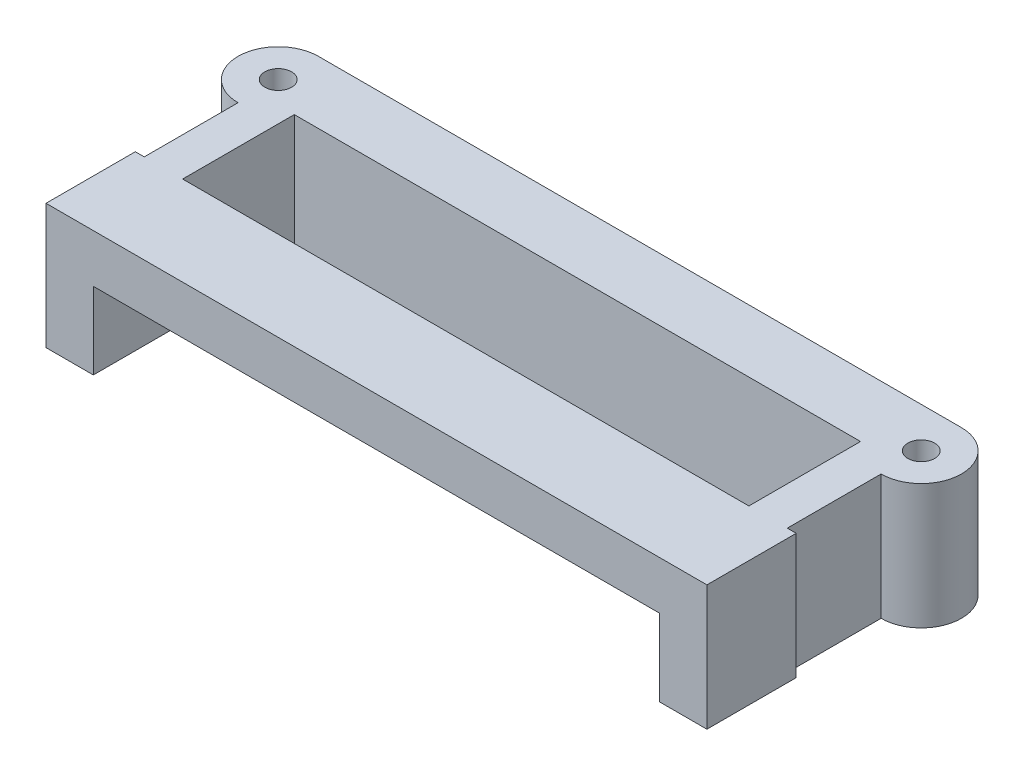
SolidWorks part; units mm, degrees
ref_plane "Спереди" through (0, 0, 0) normal (0, 0, 1) x (1, 0, 0)
ref_plane "Сверху" through (0, 0, 0) normal (0, 1, 0) x (1, 0, 0)
ref_plane "Справа" through (0, 0, 0) normal (1, 0, 0) x (0, 0, -1)
other "Configuration Table"
sketch "Эскиз1" plane through (0, 0, 0) normal (0, 1, 0) x (1, 0, 0)
  line L1 (0, 0) -> (1, 0)
  line L2 (0, 0) -> (0, -10)
  line L3 (0, -10) -> (74, -10)
  line L4 (74, 0) -> (74, -10)
  line L9 (1, 10.5) -> (1, 0)
  line L10 (73, 0) -> (74, 0)
  line L11 (73, 10.5) -> (73, 0)
  line L14 (5.3, 12.5) -> (5.3, 0)
  line L15 (5.3, 0) -> (68.7, 0)
  line L16 (68.7, 12.5) -> (68.7, 0)
  line L17 (1, 19.5) -> (73, 19.5)
  line L19 (5.3, 12.5) -> (68.7, 12.5)
  circle A0 centre (1, 15) radius 1.5
  circle A1 centre (73, 15) radius 1.5
  arc A2 (1, 19.5) -> (1, 10.5) centre (1, 15) ccw
  arc A3 (73, 10.5) -> (73, 19.5) centre (73, 15) ccw
  dimension "D3" = 3
  dimension "D4" = 3
  dimension "D8" = 9
  dimension "D9" = 9
  dimension "D1" = 74
  dimension "D2" = 10
  dimension "D5" = 72
  dimension "D6" = 1
  dimension "D7" = 15
  dimension "D10" = 12.5
  dimension "D11" = 5.3
  dimension "D12" = 10
extrude "Бобышка-Вытянуть1" add sketch "Эскиз1" along normal blind 14
sketch "Эскиз2" plane through (0, 0, 0) normal (0, -1, 0) x (1, 0, 0)
  line L0 (0, 10) -> (74, 10) construction
  line L1 (5.3, 0) -> (68.7, 0)
  line L2 (5.3, 0) -> (5.3, 10)
  line L3 (5.3, 10) -> (68.7, 10)
  line L4 (68.7, 0) -> (68.7, 10)
extrude "Вырез-Вытянуть1" cut sketch "Эскиз2" against normal blind 8.6
